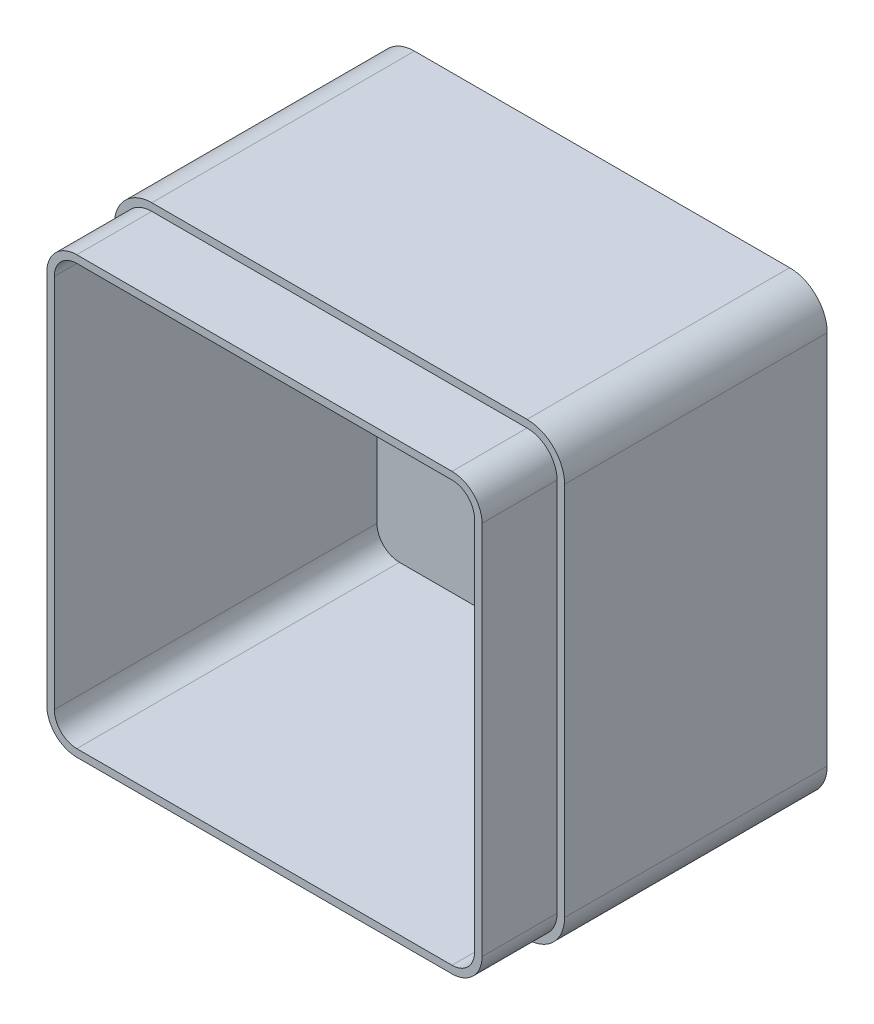
SolidWorks part; units mm, degrees
ref_plane "Спереди" through (0, 0, 0) normal (0, 0, 1) x (1, 0, 0)
ref_plane "Сверху" through (0, 0, 0) normal (0, 1, 0) x (1, 0, 0)
ref_plane "Справа" through (0, 0, 0) normal (1, 0, 0) x (0, 0, -1)
other "Configuration Table"
sketch "Эскиз1" plane through (0, 0, 0) normal (0, 0, 1) x (1, 0, 0)
  line L5 (0, 0) -> (120, 0)
  line L6 (0, 0) -> (0, 120)
  line L7 (0, 120) -> (120, 120)
  line L8 (120, 0) -> (120, 120)
  dimension "D1" = 120
  dimension "D2" = 120
extrude "Бобышка-Вытянуть1" add sketch "Эскиз1" along normal blind 90
fillet "Скругление1" radius 10 4 edges at (0, 0, 45) (120, 0, 45) (0, 120, 45) (120, 120, 45)
shell "Оболочка1" thickness 4
sketch "Эскиз5" plane through (0, 0, 90) normal (0, 0, 1) x (1, 0, 0)
  line L0 (2, 110) -> (2, 10)
  line L1 (10, 2) -> (110, 2)
  line L2 (118, 10) -> (118, 110)
  line L3 (110, 118) -> (10, 118)
  line L4 (0, 110) -> (0, 10)
  line L5 (10, 0) -> (110, 0)
  line L6 (120, 10) -> (120, 110)
  line L7 (110, 120) -> (10, 120)
  line L8 (0, 110) -> (0, 10)
  line L9 (10, 0) -> (110, 0)
  line L10 (120, 10) -> (120, 110)
  line L11 (110, 120) -> (10, 120)
  arc A0 (2, 10) -> (10, 2) centre (10, 10) ccw
  arc A1 (110, 2) -> (118, 10) centre (110, 10) ccw
  arc A2 (118, 110) -> (110, 118) centre (110, 110) ccw
  arc A3 (10, 118) -> (2, 110) centre (10, 110) ccw
  arc A4 (0, 10) -> (10, 0) centre (10, 10) ccw
  arc A5 (110, 0) -> (120, 10) centre (110, 10) ccw
  arc A6 (120, 110) -> (110, 120) centre (110, 110) ccw
  arc A7 (10, 120) -> (0, 110) centre (10, 110) ccw
  arc A8 (0, 10) -> (10, 0) centre (10, 10) ccw
  arc A9 (110, 0) -> (120, 10) centre (110, 10) ccw
  arc A10 (120, 110) -> (110, 120) centre (110, 110) ccw
  arc A11 (10, 120) -> (0, 110) centre (10, 110) ccw
  dimension "D1" = 0
  dimension "D2" = 2
extrude "Вырез-Вытянуть3" cut sketch "Эскиз5" against normal blind 20
